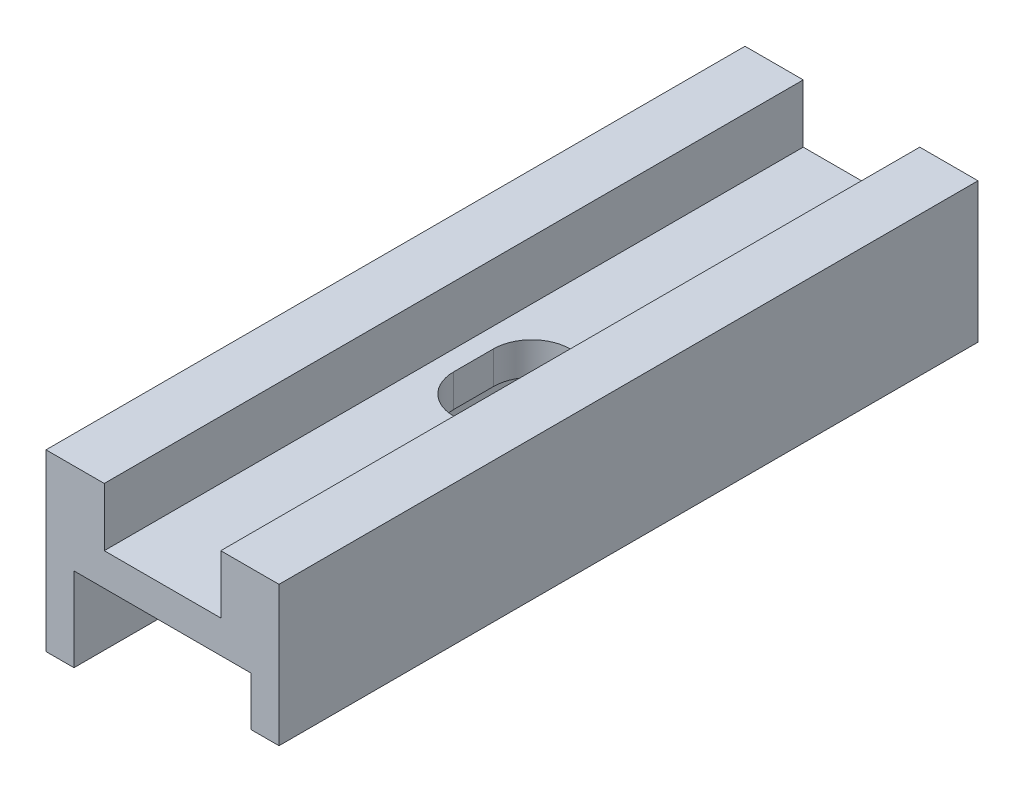
SolidWorks part; units mm, degrees
ref_plane "Front" through (0, 0, 0) normal (0, 0, 1) x (1, 0, 0)
ref_plane "Top" through (0, 0, 0) normal (0, 1, 0) x (1, 0, 0)
ref_plane "Right" through (0, 0, 0) normal (1, 0, 0) x (0, 0, -1)
sketch "Sketch1" plane through (0, 0, 0) normal (0, 0, 1) x (1, 0, 0)
  line L0 (-12.7, 7.62) -> (-6.35, 7.62)
  line L1 (-6.35, 7.62) -> (-6.35, 1.27)
  line L2 (-6.35, 1.27) -> (6.35, 1.27)
  line L3 (6.35, 1.27) -> (6.35, 7.62)
  line L4 (6.35, 7.62) -> (12.7, 7.62)
  line L5 (12.7, 7.62) -> (12.7, -7.62)
  line L6 (12.7, -7.62) -> (9.652, -7.62)
  line L7 (9.652, -7.62) -> (9.652, -2.286)
  line L8 (9.652, -2.286) -> (-9.652, -2.286)
  line L9 (-9.652, -2.286) -> (-9.652, -11.43)
  line L10 (-9.652, -11.43) -> (-12.7, -11.43)
  line L11 (-12.7, -11.43) -> (-12.7, 7.62)
  line L12 (0, -50) -> (0, 50) construction
  line L13 (50, 0) -> (-50, 0) construction
  point P12 (0, 1.27)
  point P15 (12.7, 0)
  point P18 (11.176, -7.62)
  point P19 (6.35, 4.445)
  dimension "D1" = 12.7
  dimension "D2" = 3.048
  dimension "D3" = 25.4
  dimension "D4" = 15.24
  dimension "D5" = 19.05
  dimension "D6" = 3.556
  dimension "D7" = 6.35
extrude "Boss-Extrude1" add sketch "Sketch1" along normal mid plane 76.2 contours L4 L5 L6 L7 L8 L9 L10 L11 L0 L1 L2 L3
sketch "Sketch2" plane through (0, 1.27, 0) normal (0, 1, 0) x (1, 0, 0)
  line L0 (0, 2.159) -> (0, -2.159) construction
  line L1 (0, -50) -> (0, 50) construction
  line L2 (4.191, 2.159) -> (4.191, -2.159)
  line L3 (-4.191, 2.159) -> (-4.191, -2.159)
  line L4 (-6.35, 38.1) -> (6.35, 38.1) construction
  line L5 (-6.35, -38.1) -> (6.35, -38.1) construction
  arc A0 (4.191, 2.159) -> (-4.191, 2.159) centre (0, 2.159) ccw
  arc A1 (-4.191, -2.159) -> (4.191, -2.159) centre (0, -2.159) ccw
  point P5 (0, 0)
  point P12 (0, 6.35)
  point P13 (0, -6.35)
  dimension "D1" = 31.75
  dimension "D2" = 31.75
  dimension "D3" = 8.382
extrude "Cut-Extrude1" cut sketch "Sketch2" against normal up to next contours A1 L2 A0 L3
